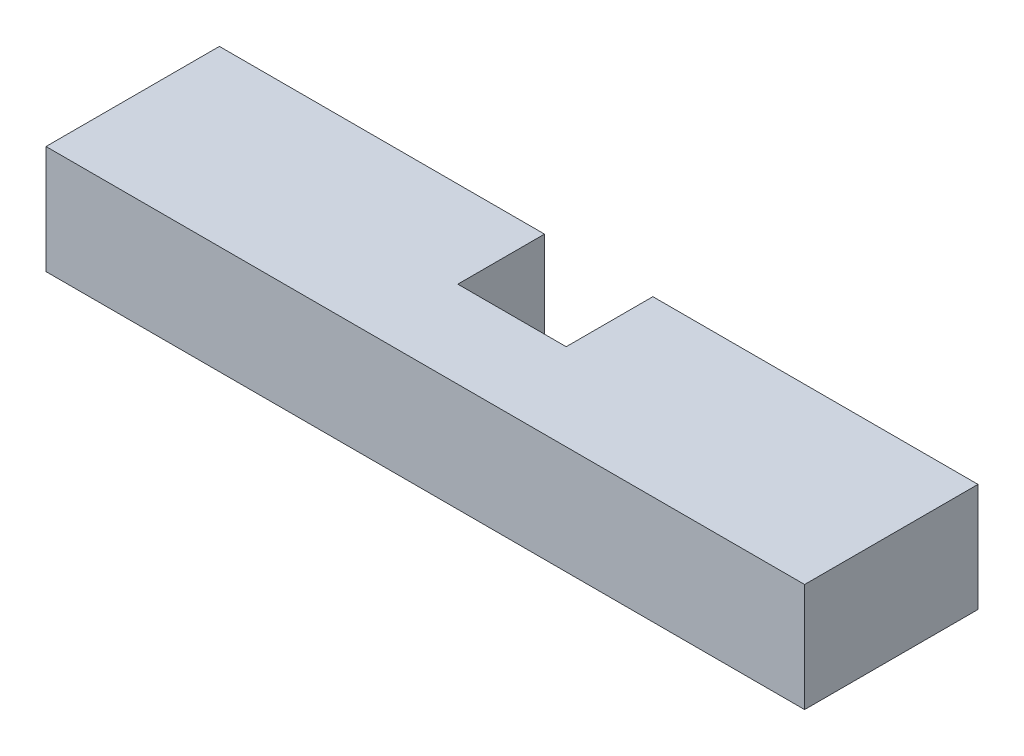
SolidWorks part; units mm, degrees
ref_plane "Front Plane" through (0, 0, 0) normal (0, 0, 1) x (1, 0, 0)
ref_plane "Top Plane" through (0, 0, 0) normal (0, 1, 0) x (1, 0, 0)
ref_plane "Right Plane" through (0, 0, 0) normal (1, 0, 0) x (0, 0, -1)
sketch "Elevator Paddle Support Strut" plane through (0, 0, 0) normal (0, 1, 0) x (1, 0, 0)
  line L0 (0, -5.08) -> (0, 0) construction
  line L1 (-22.225, -5.08) -> (22.225, -5.08)
  line L2 (-22.225, -5.08) -> (-22.225, 5.08)
  line L3 (-22.225, 5.08) -> (-3.175, 5.08)
  line L4 (22.225, -5.08) -> (22.225, 5.08)
  line L5 (-22.225, -5.08) -> (0, 0) construction
  line L6 (-22.225, 5.08) -> (-3.175, 0.7257) construction
  line L7 (-22.225, 0) -> (22.225, 0) construction
  line L8 (-3.175, 0) -> (3.175, 0)
  line L9 (-3.175, 0) -> (-3.175, 5.08)
  line L10 (3.175, 0.7257) -> (22.225, 5.08) construction
  line L11 (3.175, 0) -> (3.175, 5.08)
  line L13 (0, 0) -> (22.225, -5.08) construction
  line L14 (3.175, 5.08) -> (22.225, 5.08)
  point P0 (0, 0)
  point P8 (0, 0)
  dimension "D1" = 10.16
  dimension "D2" = 44.45
  dimension "D3" = 6.35
extrude "Boss-Extrude1" add sketch "Elevator Paddle Support Strut" along normal blind 6.35 contours L11 L8 L9 L3 L2 L1 L4
equation "\"Ball Diameter\"= 1.75in"
equation "\"Sheet Thickness\"= 0.25in"
equation "\"Screw Diameter\"= .17in"
equation "\"Robot Diameter\"= 14in"
equation "\"Castor Screw Diameter\"= 0.22in"
equation "\"Wheel Diameter\" = 4in"
equation "\"Nut Diameter\" = 8.4mm"
equation "\"Nut Height\" = 2.9mm"
equation "\"Screw Height\" = 0.55in"
equation "\"D2@Elevator Paddle Support Strut\"=\"Ball Diameter\""
equation "\"D3@Elevator Paddle Support Strut\"=\"Sheet Thickness\""
equation "\"D1@Boss-Extrude1\"=\"Sheet Thickness\""
